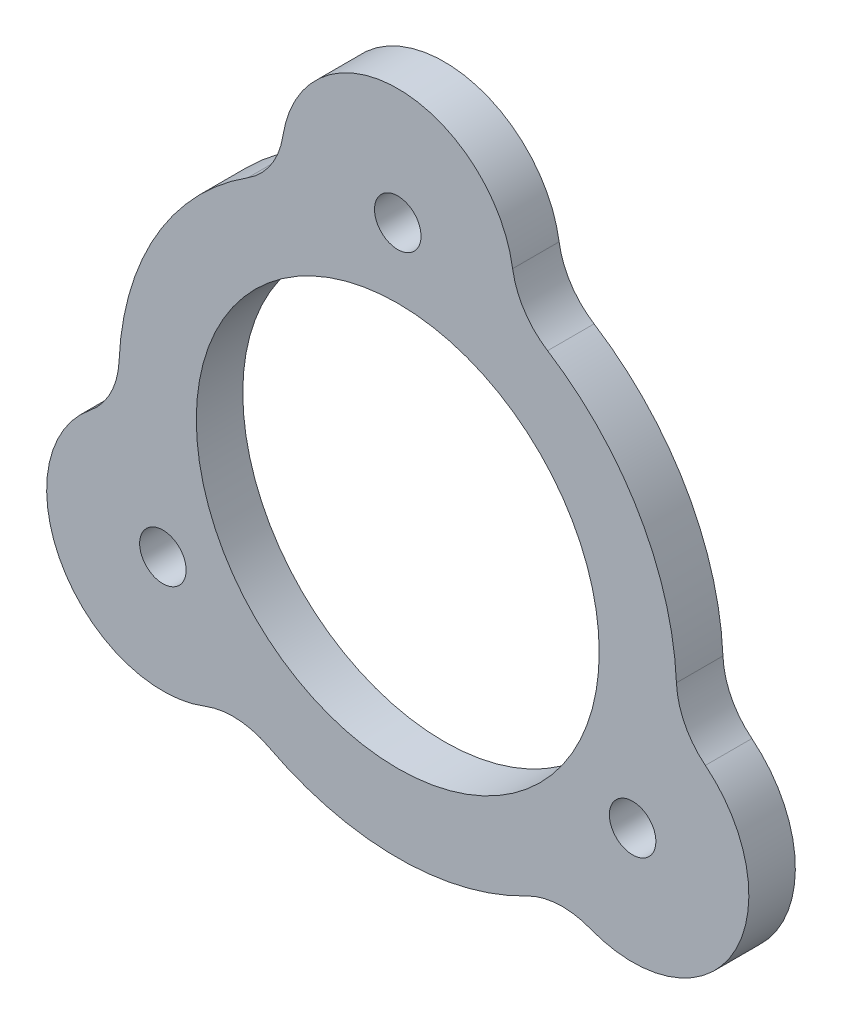
SolidWorks part; units mm, degrees
ref_plane "前视基准面" through (0, 0, 0) normal (0, 0, 1) x (1, 0, 0)
ref_plane "上视基准面" through (0, 0, 0) normal (0, 1, 0) x (1, 0, 0)
ref_plane "右视基准面" through (0, 0, 0) normal (1, 0, 0) x (0, 0, -1)
sketch "草图2" plane through (0, 0, 0) normal (0, 0, 1) x (1, 0, 0)
  line L0 (0, 0) -> (0, 17.5) construction
  line L1 (0, 0) -> (-15.1554, -8.75) construction
  line L2 (0, 0) -> (15.1554, -8.75) construction
  line L3 (0, 17.5) -> (-7.5, 17.5) construction
  line L4 (0, 17.5) -> (7.5, 17.5) construction
  line L5 (-15.1554, -8.75) -> (-18.9054, -2.2548) construction
  line L6 (-15.1554, -8.75) -> (-11.4054, -15.2452) construction
  line L7 (15.1554, -8.75) -> (18.9054, -2.2548) construction
  line L8 (15.1554, -8.75) -> (11.4054, -15.2452) construction
  circle A0 centre (0, 0) radius 17.5
  circle A1 centre (0, 0) radius 8.75
  circle A2 centre (0, 17.5) radius 7.5
  circle A3 centre (-15.1554, -8.75) radius 7.5
  circle A4 centre (15.1554, -8.75) radius 7.5
  arc A5 (-7.5, 17.5) -> (-18.9054, -2.2548) centre (-30.3109, 17.5) cw
  arc A6 (-11.4054, -15.2452) -> (11.4054, -15.2452) centre (0, -35) cw
  arc A7 (7.5, 17.5) -> (18.9054, -2.2548) centre (30.3109, 17.5) ccw
  dimension "D1" = 17.5
  dimension "D2" = 35
  dimension "D5" = 15
  dimension "D6" = 15
  dimension "D7" = 15
  dimension "D3" = 120
  dimension "D4" = 120
extrude "凸台-拉伸1" add sketch "草图2" along normal blind 3 contours A7 A0 A2 A5 A3 A6 A4 A1 | A0 A2 | A0 A2 | A0 A4 | A0 A4 | A0 A3 | A0 A3 | A0 A5 A3 | A3 A6 A0 | A0 A6 A4 | A7 A0 A4 | A2 A5 A0 | A7 A2 A0
sketch "草图3" plane through (0, 0, 3) normal (0, 0, 1) x (1, 0, 0)
  circle A0 centre (0, 17.5) radius 1.5
  dimension "D1" = 3
extrude "切除-拉伸1" cut sketch "草图3" against normal through all
pattern_circular "阵列(圆周)1" count 3 over 240 about axis through (0, 0, 0) along (0, 0, 1) of "切除-拉伸1"
sketch "草图4" plane through (0, 0, 3) normal (0, 0, 1) x (1, 0, 0)
  circle A0 centre (0, 0) radius 18
  dimension "D1" = 36
extrude "凸台-拉伸2" add sketch "草图4" against normal up to surface (3 mm away) up to face at (-15.9054, -7.451, 0)
fillet "圆角1" radius 5 6 edges at (17.9238, -1.6545, 1.5) (7.529, 16.3497, 1.5) (-7.529, 16.3497, 1.5) (-17.9238, -1.6545, 1.5) (-10.3948, -14.6952, 1.5) (10.3948, -14.6952, 1.5)
sketch "草图5" plane through (0, 0, 3) normal (0, 0, 1) x (1, 0, 0)
  circle A0 centre (0, 0) radius 13
  dimension "D1" = 26
extrude "切除-拉伸2" cut sketch "草图5" against normal through all
sketch "草图6" plane through (0, 0, 3) normal (0, 0, 1) x (1, 0, 0)
  circle A0 centre (0, 17.5) radius 1.5
extrude "切除-拉伸3" cut sketch "草图6" against normal through all
pattern_circular "阵列(圆周)2" count 3 over 240 about axis through (0, 0, -50.9117) along (0, 0, 1) of "切除-拉伸1"
